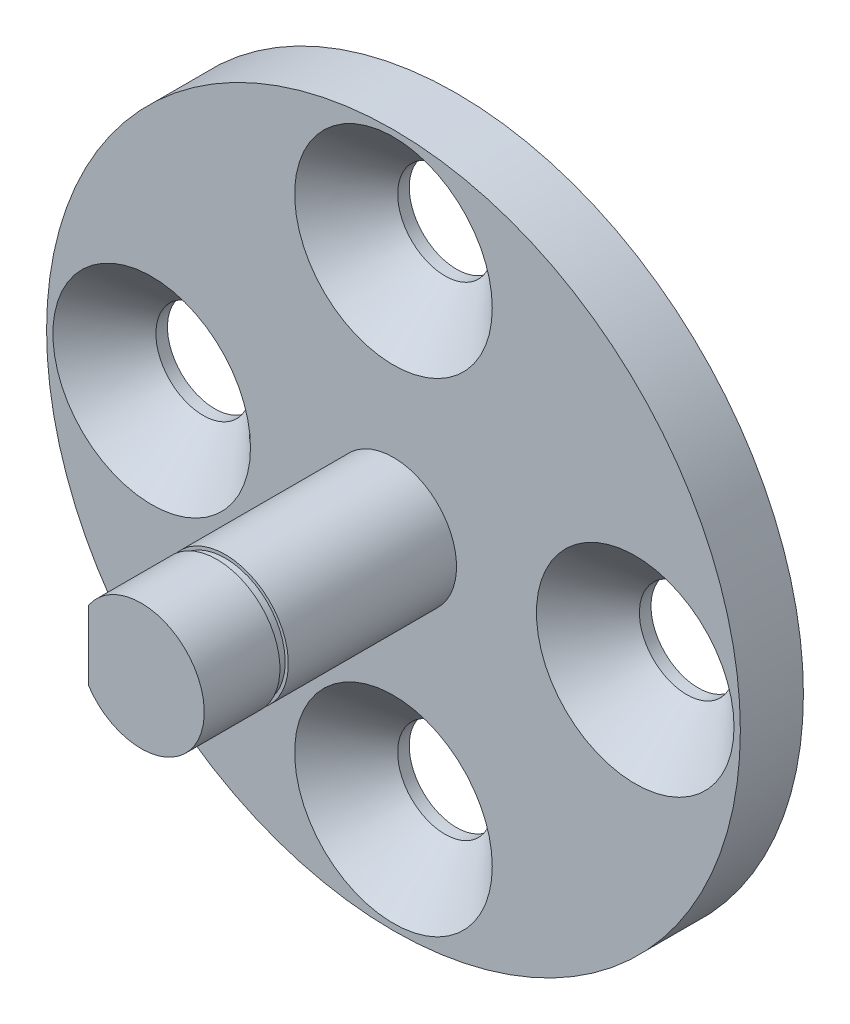
SolidWorks part; units mm, degrees
material "Alloy Steel"
ref_plane "Front Plane" through (0, 0, 0) normal (0, 0, 1) x (1, 0, 0)
ref_plane "Top Plane" through (0, 0, 0) normal (0, 1, 0) x (1, 0, 0)
ref_plane "Right Plane" through (0, 0, 0) normal (1, 0, 0) x (0, 0, -1)
sketch "Sketch1" plane through (0, 0, 0) normal (0, 0, 1) x (1, 0, 0)
  circle A0 centre (0, 0) radius 16.5
  dimension "D1" = 33
extrude "Boss-Extrude1" add sketch "Sketch1" along normal blind 3
sketch "Sketch2" plane through (0, 0, 3) normal (0, 0, 1) x (1, 0, 0)
  circle A0 centre (0, 0) radius 3
  dimension "D1" = 6
extrude "Boss-Extrude2" add sketch "Sketch2" along normal blind 12
sketch "Sketch3" plane through (0, 0, 3) normal (0, 0, 1) x (1, 0, 0)
  circle A0 centre (0, 0) radius 6
  dimension "D1" = 12
extrude "Boss-Extrude3" add sketch "Sketch3" along normal blind 1
sketch "Sketch4" plane through (0, 0, 15) normal (0, 0, 1) x (1, 0, 0)
  line L0 (-2.5, 1.6583) -> (-2.5, -1.6583)
  circle A0 centre (0, 0) radius 3 construction
  arc A1 (-2.5, 1.6583) -> (-2.4683, -1.7051) centre (0, 0) ccw
  circle M2 centre (0, 0) radius 3
  dimension "D1" = 2.5
extrude "Cut-Extrude1" cut sketch "Sketch4" against normal up to surface (11 mm away) contours L0 M2
sketch "Sketch5" plane through (0, 0, 3) normal (0, 0, 1) x (1, 0, 0)
  circle A0 centre (0, 0) radius 11.5 construction
  circle A1 centre (0, 11.5) radius 2
  dimension "D1" = 23
  dimension "D2" = 4
extrude "Cut-Extrude2" cut sketch "Sketch5" against normal through all
pattern_circular "CirPattern1" count 4 over 360 about axis through (0, 0, 0) along (0, 0, 1) of "Cut-Extrude2"
hole_wizard "CSK for M4 Flat Head Machine Screw1" positions "Sketch7" profile "Sketch8" countersink size "M4" standard "ANSI Metric" end condition through all
sketch "Sketch7" plane through (0, 0, 3) normal (0, 0, 1) x (1, 0, 0)
  point P0 (-11.5, 0)
  point P3 (0, 11.5)
  point P6 (11.5, 0)
  point P9 (0, -11.5)
sketch "Sketch8" plane through (-11.5, 0, 3) normal (1, 0, 0) x (0, -1, 0)
  line L0 (0, 0) -> (0, 3)
  line L1 (0, 3) -> (2.25, 3)
  line L2 (2.25, 3) -> (2.25, 2.45)
  line L3 (2.25, 2.45) -> (4.7, 0)
  line L5 (4.7, 0) -> (0, 0)
  line L6 (-2.25, 2.45) -> (-4.7, 0) construction
  line L11 (0, -6.35) -> (0, 107.95) construction
  dimension "Thru Hole Dia." = 4.5
  dimension "Thru Hole Depth" = 3
  dimension "Near C'Sink Dia." = 9.4
  dimension "Near C'Sink Angle" = 90
sketch "Sketch9" plane through (0, 0, 4) normal (0, 0, 1) x (1, 0, 0)
  line L0 (-2.5, -1.6583) -> (-2.5, 1.6583) construction
  line L1 (-2.5, -1.6583) -> (-2.5, 1.6583)
  arc A1 (-2.5, -1.6583) -> (-2.5, 1.6583) centre (0, 0) ccw construction
  circle A2 centre (0, 0) radius 6
  circle A3 centre (0, 0) radius 6
  arc A4 (-2.5, -1.6583) -> (-2.5, 1.6583) centre (0, 0) ccw
  dimension "D1" = 0
extrude "Cut-Extrude3" cut sketch "Sketch9" against normal up to surface (1 mm away) up to face at (-6.8, 0, 3)
sketch "Sketch10" plane through (0, 0, 0) normal (0, 1, 0) x (1, 0, 0)
  line L0 (0, 0) -> (0, -10.4426) construction
  line L1 (3, -15) -> (3, -3) construction
  line L2 (3.15, -11) -> (2.85, -11)
  line L3 (3.15, -11) -> (3.15, -11.4)
  line L4 (3.15, -11.4) -> (2.85, -11.4)
  line L5 (2.85, -11) -> (2.85, -11.4)
  line L6 (3.15, -11) -> (2.85, -11.4) construction
  line L7 (3.15, -11.4) -> (2.85, -11) construction
  line L8 (-16.5, -3) -> (16.5, -3) construction
  point P3 (3, -11.2)
  point P10 (3, -11.4)
  dimension "D1" = 2.85
  dimension "D2" = 0.4
  dimension "D3" = 8
revolve "Cut-Revolve1" cut sketch "Sketch10" angle 360 about L0
